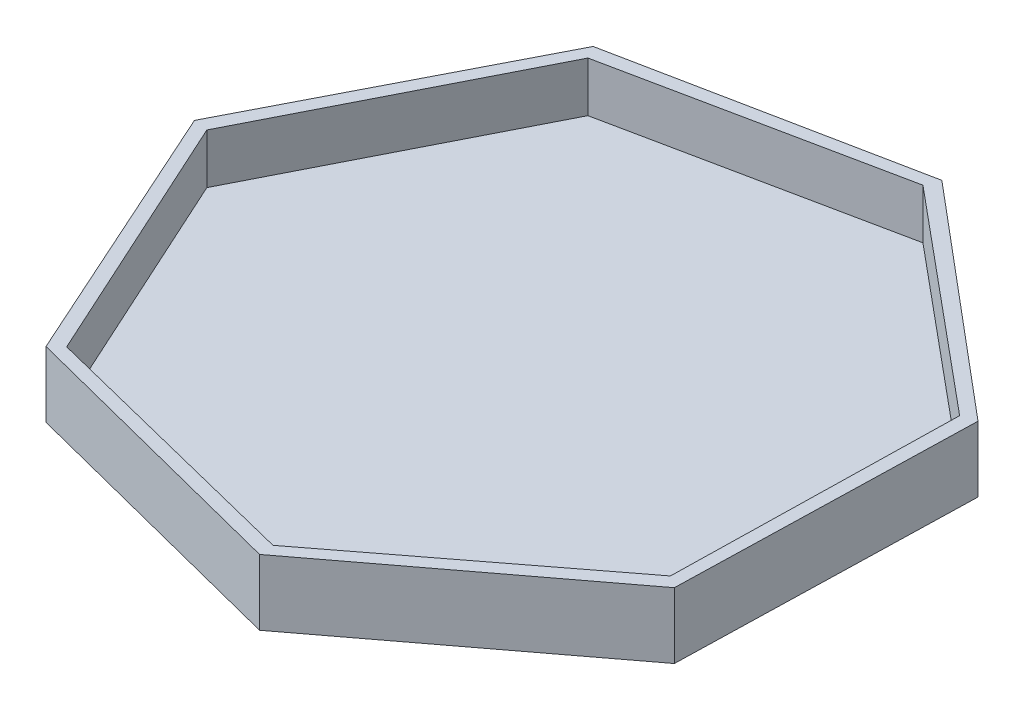
SolidWorks part; units mm, degrees
ref_plane "Front Plane" through (0, 0, 0) normal (0, 0, 1) x (1, 0, 0)
ref_plane "Top Plane" through (0, 0, 0) normal (0, 1, 0) x (1, 0, 0)
ref_plane "Right Plane" through (0, 0, 0) normal (1, 0, 0) x (0, 0, -1)
sketch "Sketch1" plane through (0, 0, 0) normal (0, 1, 0) x (1, 0, 0)
  line L8 (-16.7117, -19.8816) -> (5.1245, -25.4617)
  line L9 (5.1245, -25.4617) -> (23.1018, -11.8686)
  line L10 (23.1018, -11.8686) -> (23.683, 10.6617)
  line L11 (23.683, 10.6617) -> (6.4304, 25.1636)
  line L12 (6.4304, 25.1636) -> (-15.6644, 20.7167)
  line L13 (-15.6644, 20.7167) -> (-25.9636, 0.6698)
  line L14 (-25.9636, 0.6698) -> (-16.7117, -19.8816)
  circle A1 centre (0, 0) radius 23.4002 construction
extrude "Boss-Extrude1" add sketch "Sketch1" along normal blind 5 contours L8 L9 L10 L11 L12 L13 L14
sketch "Sketch5" plane through (0, 5, 0) normal (0, 1, 0) x (1, 0, 0)
  line L1 (6.0297, 24.1237) -> (-15.1012, 19.7551)
  line L2 (-15.1012, 19.7551) -> (-24.8606, 0.5105)
  line L3 (-24.8606, 0.5105) -> (-15.8995, -19.1185)
  line L4 (-15.8995, -19.1185) -> (5.0343, -24.3509)
  line L5 (5.0343, -24.3509) -> (22.1772, -11.2466)
  line L6 (22.1772, -11.2466) -> (22.6201, 10.3267)
  line L7 (22.6201, 10.3267) -> (6.0297, 24.1237)
  circle A0 centre (0, 0) radius 22.4034 construction
extrude "Cut-Extrude1" cut sketch "Sketch5" against normal blind 3.8
